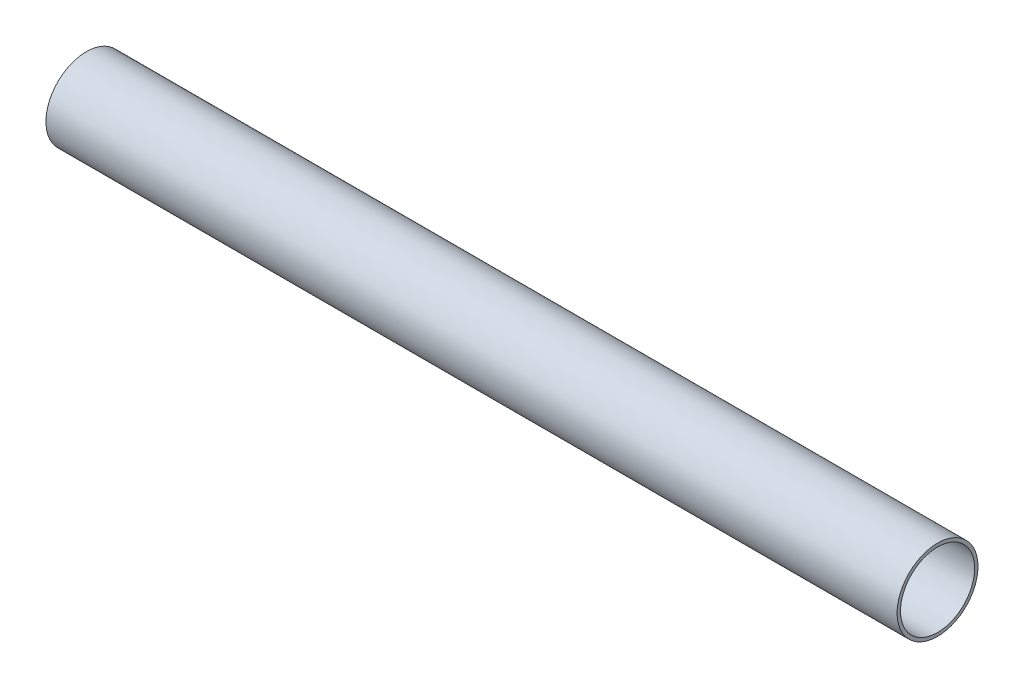
SolidWorks part; units mm, degrees
material "Rubber"
ref_plane "Front Plane" through (0, 0, 0) normal (0, 0, 1) x (1, 0, 0)
ref_plane "Top Plane" through (0, 0, 0) normal (0, 1, 0) x (1, 0, 0)
ref_plane "Right Plane" through (0, 0, 0) normal (1, 0, 0) x (0, 0, -1)
sketch "Sketch1" plane through (0, 0, 0) normal (1, 0, 0) x (0, 0, -1)
  circle A0 centre (0, 0) radius 17.4625
  circle A1 centre (0, 0) radius 19.05
  dimension "D1" = 34.925
  dimension "D2" = 38.1
extrude "Boss-Extrude1" add sketch "Sketch1" along normal blind 400.939
